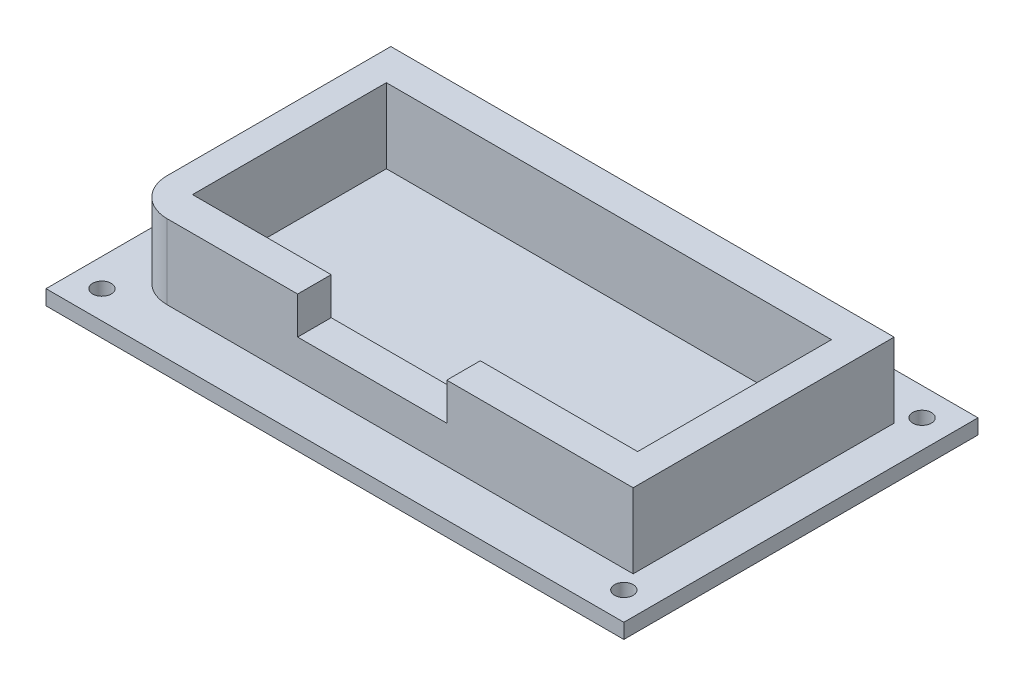
SolidWorks part; units mm, degrees
ref_plane "Front Plane" through (0, 0, 0) normal (0, 0, 1) x (1, 0, 0)
ref_plane "Top Plane" through (0, 0, 0) normal (0, 1, 0) x (1, 0, 0)
ref_plane "Right Plane" through (0, 0, 0) normal (1, 0, 0) x (0, 0, -1)
sketch "Sketch1" plane through (0, 0, 0) normal (0, 1, 0) x (1, 0, 0)
  line L1 (98.425, -60.325) -> (-98.425, -60.325)
  line L2 (98.425, -60.325) -> (98.425, 60.325)
  line L3 (98.425, 60.325) -> (-98.425, 60.325)
  line L4 (-98.425, -60.325) -> (-98.425, 60.325)
  line L5 (0, 60.325) -> (0, -60.325) construction
  line L6 (98.425, 0) -> (-98.425, 0) construction
  line L7 (88.9, -50.8) -> (-88.9, -50.8)
  line L8 (88.9, -50.8) -> (88.9, 50.8)
  line L9 (88.9, 50.8) -> (-88.9, 50.8)
  line L10 (-88.9, -50.8) -> (-88.9, 50.8)
  line L11 (0, 50.8) -> (0, -50.8) construction
  line L12 (88.9, 0) -> (-88.9, 0) construction
  circle A0 centre (-88.9, -50.8) radius 3.175
  circle A1 centre (88.9, -50.8) radius 3.175
  circle A2 centre (-88.9, 50.8) radius 3.175
  circle A3 centre (88.9, 50.8) radius 3.175
  point P0 (0, 0)
  point P4 (0, 0)
  dimension "D1" = 196.85
  dimension "D2" = 120.65
  dimension "D3" = 9.525
  dimension "D4" = 9.525
extrude "Boss-Extrude2" add sketch "Sketch1" along normal blind 5.08 contours L4 L1 L2 L3 A3 L8 A1 L7 A0 L10 A2 L9 | A3 L9 A2 L10 A0 L7 A1 L8
sketch "Sketch4" plane through (0, 5.08, 0) normal (0, 1, 0) x (1, 0, 0)
  line L1 (-85.725, -44.45) -> (85.725, -44.45)
  line L2 (-85.725, -44.45) -> (-85.725, 44.45)
  line L3 (-85.725, 44.45) -> (85.725, 44.45)
  line L4 (85.725, -44.45) -> (85.725, 44.45)
  line L5 (0, 44.45) -> (0, -44.45) construction
  line L6 (-85.725, 0) -> (85.725, 0) construction
  line L7 (75.819, -33.02) -> (-75.819, -33.02)
  line L8 (75.819, -33.02) -> (75.819, 33.02)
  line L9 (75.819, 33.02) -> (-75.819, 33.02)
  line L10 (-75.819, -33.02) -> (-75.819, 33.02)
  line L11 (0, 33.02) -> (0, -33.02) construction
  line L12 (75.819, 0) -> (-75.819, 0) construction
  point P0 (0, 0)
  point P4 (0, 0)
  dimension "D1" = 88.9
  dimension "D2" = 171.45
  dimension "D3" = 66.04
  dimension "D4" = 151.638
extrude "Boss-Extrude3" add sketch "Sketch4" along normal blind 25.4
fillet "Fillet4" radius 12.7 1 edges at (-85.725, 17.78, 44.45)
sketch "Sketch7" plane through (0, 0, 33.02) normal (0, 0, -1) x (-1, 0, 0)
  line L0 (75.819, 30.48) -> (-75.819, 30.48) construction
  line L1 (28.577, 30.48) -> (-22.223, 30.48)
  line L2 (28.577, 30.48) -> (28.577, 17.78)
  line L3 (28.577, 17.78) -> (-22.223, 17.78)
  line L4 (-22.223, 30.48) -> (-22.223, 17.78)
  point P6 (3.177, 30.48)
  dimension "D1" = 12.7
  dimension "D2" = 50.8
extrude "Cut-Extrude1" cut sketch "Sketch7" against normal up to next
